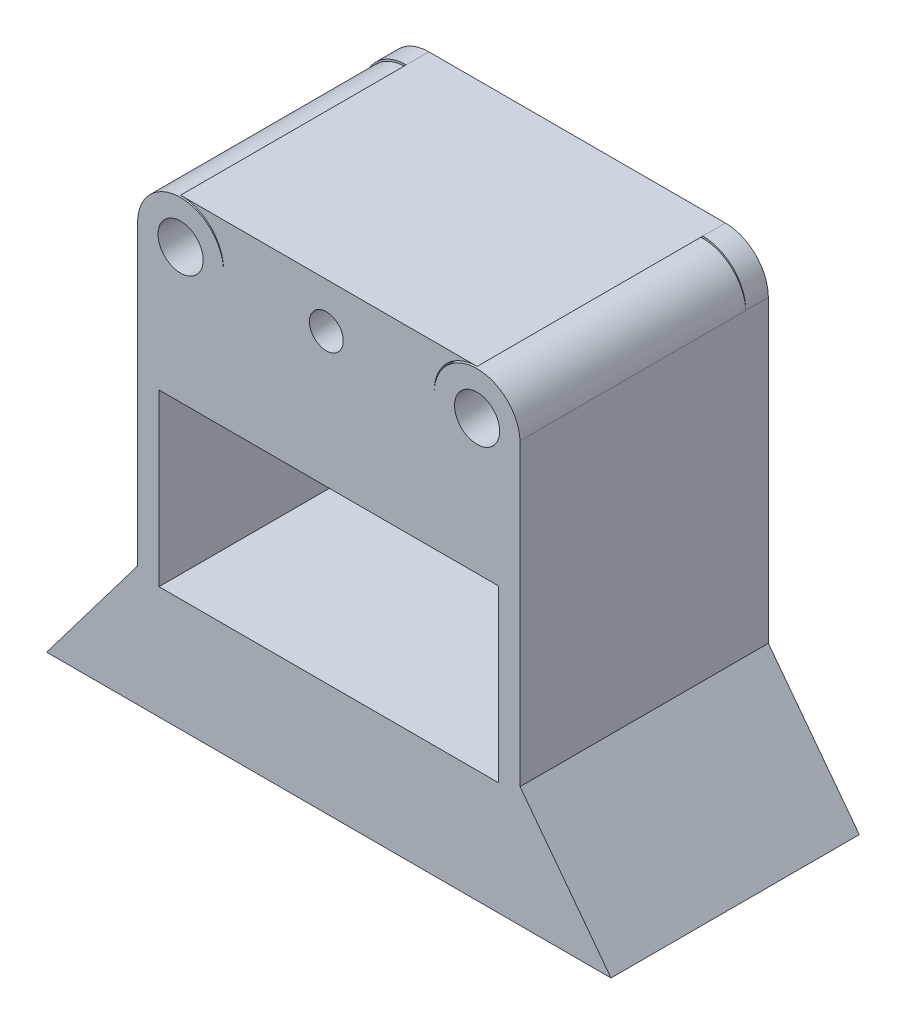
SolidWorks part; units mm, degrees
ref_plane "Front Plane" through (0, 0, 0) normal (0, 0, 1) x (1, 0, 0)
ref_plane "Top Plane" through (0, 0, 0) normal (0, 1, 0) x (1, 0, 0)
ref_plane "Right Plane" through (0, 0, 0) normal (1, 0, 0) x (0, 0, -1)
sketch "Sketch1" plane through (0, 0, 0) normal (0, 0, 1) x (1, 0, 0)
  line L0 (0, 0) -> (0, 54.0315) construction
  line L1 (-38.227, -19.177) -> (38.227, -19.177)
  line L2 (-38.227, -19.177) -> (-38.227, 19.177)
  line L3 (-38.227, 19.177) -> (38.227, 19.177)
  line L4 (38.227, -19.177) -> (38.227, 19.177)
  line L5 (-38.227, -19.177) -> (38.227, 19.177) construction
  line L6 (-38.227, 19.177) -> (38.227, -19.177) construction
  line L7 (0, 54.0315) -> (0, -50.3288) construction
  line L8 (-38.227, 7.4711) -> (-38.227, 58.2157) construction
  line L9 (-43.03, -17.5223) -> (-43.03, 19.177)
  line L10 (-63.5, -44.577) -> (63.5, -44.577)
  line L11 (-43.03, -17.5223) -> (-63.5, -44.577)
  line L12 (-43.03, -17.5223) -> (-43.03, 56.2622) construction
  line L13 (-43.03, 19.177) -> (-43.03, 49.8911)
  line L14 (-23.6995, 49.9018) -> (0, 24.257)
  line L15 (43.03, -17.5223) -> (63.5, -44.577)
  line L16 (43.03, 19.177) -> (43.03, 49.8911)
  line L17 (43.03, -17.5223) -> (43.03, 19.177)
  line L18 (23.6995, 49.9018) -> (0, 24.257)
  circle A0 centre (-33.3645, 49.4395) radius 4.8625
  circle A1 centre (33.3645, 49.4395) radius 4.8625
  arc A2 (-43.03, 49.8911) -> (-23.6995, 49.9018) centre (-33.3645, 49.4395) cw
  arc A3 (43.03, 49.8911) -> (23.6995, 49.9018) centre (33.3645, 49.4395) ccw
  point P0 (0, 0)
  point P11 (-33.3645, 44.577)
  point P14 (-38.227, 49.4395)
  point P24 (0, 24.257)
  dimension "D3" = 9.725
  dimension "D1" = 76.454
  dimension "D2" = 38.354
  dimension "D4" = 0
  dimension "D5" = 25.4
  dimension "D6" = 5.08
  dimension "D7" = 63.5
  dimension "D9" = 25.4
  dimension "D10" = 5.08
extrude "Boss-Extrude1" add sketch "Sketch1" along normal blind 50.8
sketch "Sketch2" plane through (0, 0, 0) normal (0, 0, -1) x (-1, 0, 0)
  line L0 (-43.03, 49.8911) -> (-43.03, -17.5223)
  line L1 (-43.03, -17.5223) -> (-63.5, -44.577)
  line L2 (-63.5, -44.577) -> (63.5, -44.577)
  line L3 (63.5, -44.577) -> (43.03, -17.5223)
  line L4 (43.03, -17.5223) -> (43.03, 49.8911)
  line L5 (23.6995, 49.9018) -> (0, 24.257)
  line L6 (0, 24.257) -> (-23.6995, 49.9018)
  arc A0 (-43.03, 49.8911) -> (-23.6995, 49.9018) centre (-33.3648, 49.8911) cw
  arc A1 (23.6995, 49.9018) -> (43.03, 49.8911) centre (33.3648, 49.8911) cw
extrude "Boss-Extrude2" add sketch "Sketch2" along normal blind 5.08
sketch "Sketch3" plane through (0, 0, -5.08) normal (0, 0, -1) x (-1, 0, 0)
  line L0 (-33.3701, 59.5563) -> (33.3701, 59.5563)
  line L1 (-23.6995, 49.9018) -> (0, 24.257)
  line L2 (0, 24.257) -> (23.6995, 49.9018)
  arc A0 (-23.6995, 49.9018) -> (-43.03, 49.8911) centre (-33.3648, 49.8911) ccw construction
  arc A1 (43.03, 49.8911) -> (23.6995, 49.9018) centre (33.3648, 49.8911) ccw construction
  arc A2 (-33.3701, 59.5563) -> (-23.6995, 49.9018) centre (-33.3701, 49.8857) cw
  arc A3 (23.6995, 49.9018) -> (33.3701, 59.5563) centre (33.3701, 49.8857) cw
extrude "Boss-Extrude3" add sketch "Sketch3" against normal up to surface (55.88 mm away) up to face at (-28.502, 49.4395, 50.8)
sketch "Sketch4" plane through (0, 0, 50.8) normal (0, 0, 1) x (1, 0, 0)
  circle A0 centre (-0.5696, 49.4395) radius 3.429
  dimension "D1" = 0
extrude "Cut-Extrude1" cut sketch "Sketch4" against normal blind 50.8
sketch "Sketch5" plane through (0, 0, 50.8) normal (0, 0, 1) x (1, 0, 0)
  circle A0 centre (-0.5696, 49.4395) radius 3.81
extrude "Cut-Extrude2" cut sketch "Sketch5" against normal up to surface (50.8 mm away) up to face at (2.8594, 49.4395, 0)
sketch "Sketch6" plane through (0, 0, 50.8) normal (0, 0, 1) x (1, 0, 0)
  circle A0 centre (-33.3645, 49.4395) radius 5.08
  circle A1 centre (33.3645, 49.4395) radius 5.08
extrude "Cut-Extrude3" cut sketch "Sketch6" against normal up to surface (50.8 mm away) up to face at (-28.502, 49.4395, 0)
